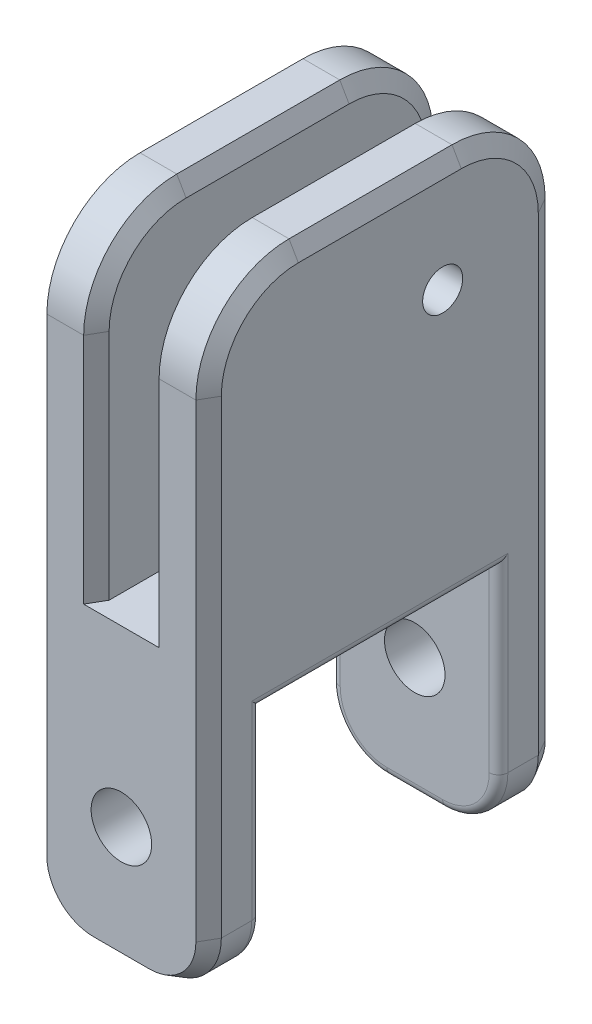
SolidWorks part; units mm, degrees
ref_plane "Front Plane" through (0, 0, 0) normal (0, 0, 1) x (1, 0, 0)
ref_plane "Top Plane" through (0, 0, 0) normal (0, 1, 0) x (1, 0, 0)
ref_plane "Right Plane" through (0, 0, 0) normal (1, 0, 0) x (0, 0, -1)
sketch "Sketch1" plane through (0, 0, 0) normal (0, 0, 1) x (1, 0, 0)
  line L1 (-9, -12.7) -> (9, -12.7)
  line L2 (-9, -12.7) -> (-9, 12.7)
  line L3 (-9, 12.7) -> (9, 12.7)
  line L4 (9, -12.7) -> (9, 12.7)
  line L5 (-9, -12.7) -> (9, 12.7) construction
  line L6 (-9, 12.7) -> (9, -12.7) construction
  circle A0 centre (0, 0) radius 3.25
  point P0 (0, 0)
  dimension "D3" = 6.5
  dimension "D1" = 25.4
  dimension "D2" = 18
extrude "Boss-Extrude1" add sketch "Sketch1" along normal blind 6
sketch "Sketch2" plane through (0, 12.7, 0) normal (0, 1, 0) x (1, 0, 0)
  line L0 (9, -6) -> (9, 0) construction
  line L1 (-9, -6) -> (9, -6)
  line L2 (-9, -6) -> (-9, 31.5)
  line L3 (-9, 31.5) -> (9, 31.5)
  line L4 (9, -6) -> (9, 31.5)
  dimension "D1" = 37.5
extrude "Boss-Extrude2" add sketch "Sketch2" along normal blind 6
ref_plane "Plane1" through (0, 0, -12.75) normal (0, 0, 1) x (1, 0, 0)
mirror "Mirror1" about plane through (0, 0, -12.75) normal (0, 0, 1) of "Boss-Extrude1"
sketch "Sketch3" plane through (0, 18.7, 0) normal (0, 1, 0) x (1, 0, 0)
  line L0 (-9, -6) -> (9, -6) construction
  line L1 (9, 31.5) -> (3.05, 31.5)
  line L2 (9, 31.5) -> (9, -6)
  line L3 (9, -6) -> (3.05, -6)
  line L4 (3.05, 31.5) -> (3.05, -6)
  dimension "D1" = 5.95
extrude "Boss-Extrude3" add sketch "Sketch3" along normal blind 35
mirror "Mirror2" about plane through (0, 0, 0) normal (1, 0, 0) of "Boss-Extrude3"
sketch "Sketch4" plane through (9, 0, 0) normal (1, 0, 0) x (0, 0, -1)
  line L0 (-6, 53.7) -> (31.5, 53.7) construction
  line L1 (31.5, 53.7) -> (31.5, -12.7) construction
  circle A0 centre (19.5, 41.7) radius 2.15
  point P5 (0, 0)
  dimension "D1" = 4.3
  dimension "D2" = 12
  dimension "D3" = 12
extrude "Cut-Extrude1" cut sketch "Sketch4" against normal through all
sketch "Sketch5" plane through (-9, 0, 0) normal (-1, 0, 0) x (0, 0, 1)
  circle A0 centre (-19.5, 41.7) radius 2.95
  dimension "D1" = 5.9
extrude "Cut-Extrude2" cut sketch "Sketch5" against normal up to next
fillet "Fillet1" radius 10 4 edges at (-6.025, 53.7, 6) (-6.025, 53.7, -31.5) (6.025, 53.7, -31.5) (6.025, 53.7, 6)
fillet "Fillet2" radius 6 4 edges at (-9, -12.7, -28.5) (9, -12.7, -28.5) (-9, -12.7, 3) (9, -12.7, 3)
chamfer "Chamfer1" distance 1 angle 60 10 edges at (3.05, 31.2, -31.5) (3.05, 50.7711, -28.5711) (3.05, 53.7, -12.75) (3.05, 50.7711, 3.0711) (3.05, 31.2, 6) (-3.05, 31.2, -31.5) (-3.05, 31.2, 6) (-3.05, 50.7711, -28.5711) (-3.05, 50.7711, 3.0711) (-3.05, 53.7, -12.75)
chamfer "Chamfer2" distance 1 angle 60 16 edges at (-9, 50.7711, -28.5711) (-9, 18.5, -31.5) (-9, 53.7, -12.75) (-7.2426, -10.9426, -31.5) (-9, 50.7711, 3.0711) (0, -12.7, -31.5) (-9, 18.5, 6) (7.2426, -10.9426, -31.5) (-7.2426, -10.9426, 6) (9, 18.5, -31.5) (0, -12.7, 6) (9, 50.7711, -28.5711) (7.2426, -10.9426, 6) (9, 53.7, -12.75) (9, 18.5, 6) (9, 50.7711, 3.0711)
fillet "Fillet3" radius 1 12 edges at (-9, 3, -25.5) (-7.2426, -10.9426, -25.5) (0, -12.7, -25.5) (7.2426, -10.9426, -25.5) (-9, 3, 0) (-7.2426, -10.9426, 0) (0, -12.7, 0) (7.2426, -10.9426, 0) (9, 3, -25.5) (-9, 12.7, -12.75) (9, 3, 0) (9, 12.7, -12.75)
